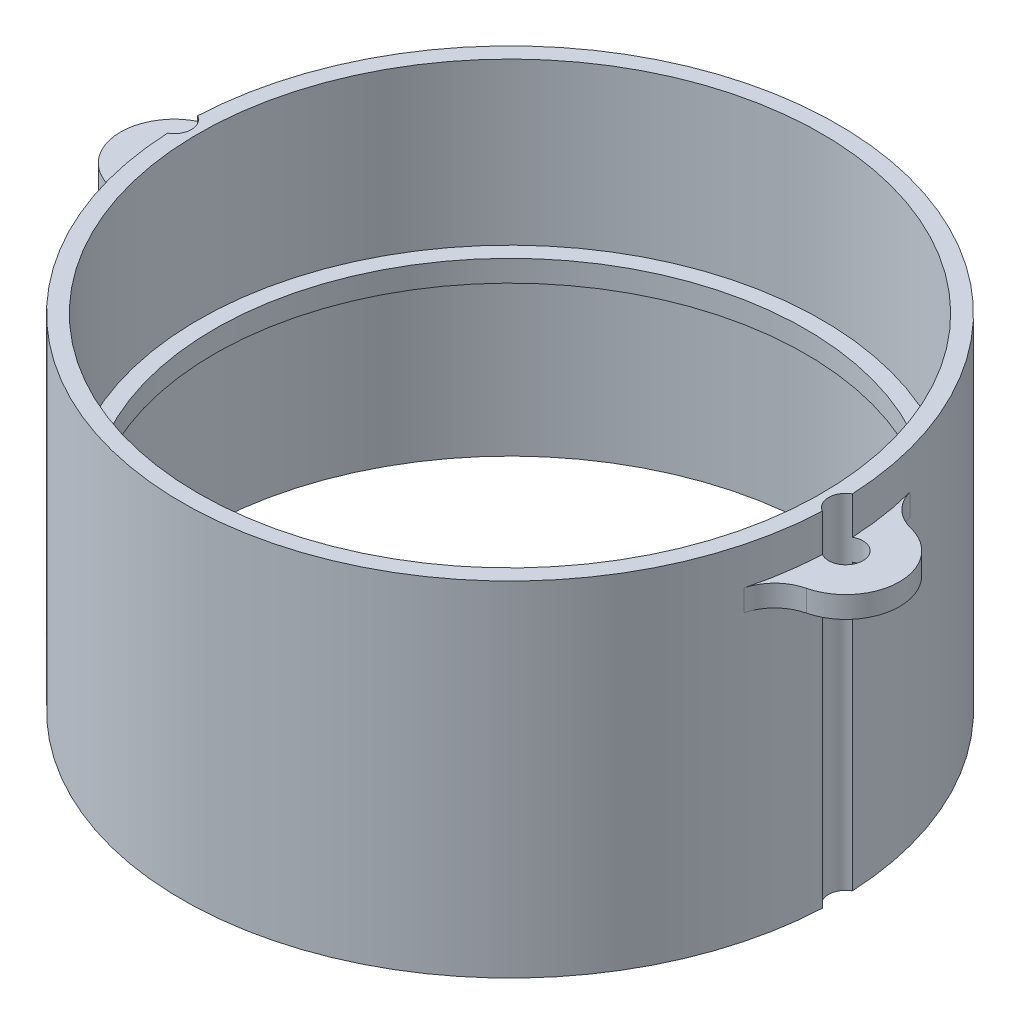
SolidWorks part; units mm, degrees
ref_plane "Front Plane" through (0, 0, 0) normal (0, 0, 1) x (1, 0, 0)
ref_plane "Top Plane" through (0, 0, 0) normal (0, 1, 0) x (1, 0, 0)
ref_plane "Right Plane" through (0, 0, 0) normal (1, 0, 0) x (0, 0, -1)
sketch "Sketch1" plane through (0, 0, 0) normal (0, 1, 0) x (1, 0, 0)
  circle A0 centre (0, 0) radius 29
  circle A1 centre (0, 0) radius 30.5
  dimension "D1" = 58
  dimension "D2" = 1.5
extrude "Boss-Extrude1" add sketch "Sketch1" along normal blind 15
sketch "Sketch2" plane through (0, 15, 0) normal (0, 1, 0) x (1, 0, 0)
  circle A0 centre (0, 0) radius 30.5
  circle A1 centre (0, 0) radius 27.5
  circle A4 centre (0, 0) radius 30.5 construction
  dimension "D1" = 3
extrude "Boss-Extrude2" add sketch "Sketch2" along normal blind 2
sketch "Sketch3" plane through (0, 17, 0) normal (0, 1, 0) x (1, 0, 0)
  circle A0 centre (0, 0) radius 30.5
  circle A1 centre (0, 0) radius 29
  circle M1 centre (0, 0) radius 30.5
  dimension "D1" = 58
  dimension "D2" = 61
extrude "Boss-Extrude3" add sketch "Sketch3" along normal blind 15 contours A1 M1
ref_plane "Plane1" through (0, 26.5, 0) normal (0, 1, 0) x (1, 0, 0)
sketch "Sketch4" plane through (0, 26.5, 0) normal (0, 1, 0) x (1, 0, 0)
  line L0 (-30.5, 0) -> (-31.25, 0)
  circle A0 centre (0, 0) radius 30.5 construction
  arc A1 (-29.5037, -7.732) -> (-29.5037, 7.732) centre (0, 0) ccw
  arc A2 (-32.4294, 4.8589) -> (-32.4294, -4.8589) centre (-31.25, 0) ccw
  arc A3 (-32.4294, -4.8589) -> (-29.5037, -7.732) centre (-33.373, -8.746) cw
  arc A4 (-32.4294, 4.8589) -> (-29.5037, 7.732) centre (-33.373, 8.746) ccw
  circle A5 centre (0, 0) radius 30.5
  dimension "D1" = 10
  dimension "D2" = 4
  dimension "D3" = 31.25
extrude "Boss-Extrude4" add sketch "Sketch4" along normal blind 2 contours A5 A4 A2 A3
sketch "Sketch5" plane through (0, 32, 0) normal (0, 1, 0) x (1, 0, 0)
  arc A0 (-32.4294, 4.8589) -> (-32.4294, -4.8589) centre (-31.25, 0) ccw construction
  arc A1 (-32.4294, 4.8589) -> (-32.4294, -4.8589) centre (-31.25, 0) ccw
  circle A2 centre (-31.25, 0) radius 1.6
  circle M1 centre (0, 0) radius 29
  circle M2 centre (0, 0) radius 30.5
  dimension "D1" = 3.2
extrude "Cut-Extrude1" cut sketch "Sketch5" against normal blind 40 contours A2 M2 M1 | A2 M2
mirror "Mirror1" about plane through (0, 0, 0) normal (1, 0, 0) of "Cut-Extrude1", "Boss-Extrude4"
